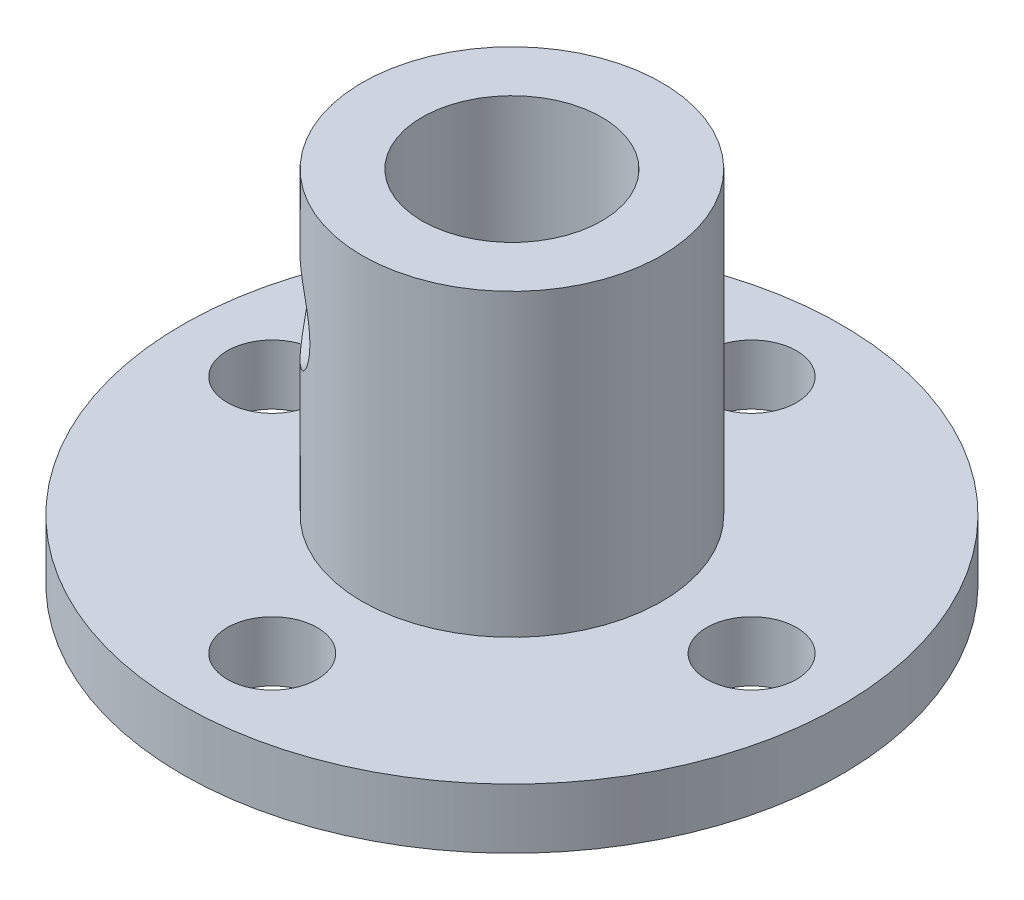
SolidWorks part; units mm, degrees
material "AISI Type 316L stainless steel"
ref_plane "Front Plane" through (0, 0, 0) normal (0, 0, 1) x (1, 0, 0)
ref_plane "Top Plane" through (0, 0, 0) normal (0, 1, 0) x (1, 0, 0)
ref_plane "Right Plane" through (0, 0, 0) normal (1, 0, 0) x (0, 0, -1)
sketch "Sketch1" plane through (0, 0, 0) normal (0, 1, 0) x (1, 0, 0)
  circle A0 centre (0, 0) radius 11
extrude "Boss-Extrude1" add sketch "Sketch1" along normal blind 2
sketch "Sketch2" plane through (0, 2, 0) normal (0, 1, 0) x (1, 0, 0)
  circle A0 centre (0, 0) radius 5
extrude "Boss-Extrude2" add sketch "Sketch2" along normal blind 10
sketch "Sketch3" plane through (0, 12, 0) normal (0, 1, 0) x (1, 0, 0)
  circle A0 centre (0, 0) radius 3
extrude "Cut-Extrude1" cut sketch "Sketch3" against normal blind 20
sketch "Sketch5" plane through (0, 0, 0) normal (0, -1, 0) x (1, 0, 0)
  line L0 (11, 0) -> (-11, 0) construction
  line L1 (0, 11) -> (0, -11) construction
  circle A0 centre (0, 0) radius 11 construction
  circle A1 centre (0, 8) radius 1.5
  circle A2 centre (0, -8) radius 1.5
  circle A3 centre (8, 0) radius 1.5
  circle A4 centre (-8, 0) radius 1.5
  dimension "D1" = 16
  dimension "D2" = 16
  dimension "D3" = 8
  dimension "D4" = 8
  dimension "D5" = 3
extrude "Cut-Extrude2" cut sketch "Sketch5" against normal blind 20
ref_plane "Plane1" through (0, 0, 0) normal (0.7071, 0, -0.7071) x (-0.7071, 0, -0.7071)
sketch "Sketch6" plane through (0, 0, 0) normal (0.7071, 0, -0.7071) x (-0.7071, 0, -0.7071)
  line L0 (0, 12) -> (0, 8) construction
  line L1 (3, 12) -> (-3, 12) construction
  circle A0 centre (0, 8) radius 1.5
  dimension "D1" = 3
  dimension "D2" = 4
extrude "Cut-Extrude3" cut sketch "Sketch6" against normal through all
sketch "Sketch7" plane through (0, 0, 0) normal (0, -1, 0) x (1, 0, 0)
  line L0 (-11, 0) -> (11, 0) construction
  circle A0 centre (0, 0) radius 11 construction
